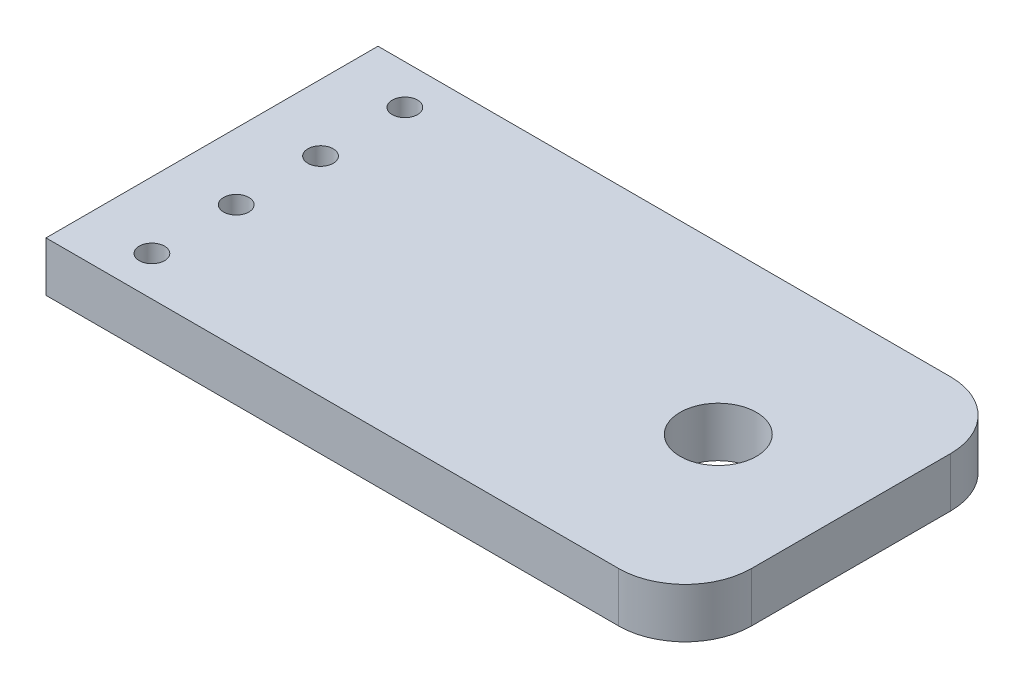
SolidWorks part; units mm, degrees
ref_plane "Front Plane" through (0, 0, 0) normal (0, 0, 1) x (1, 0, 0)
ref_plane "Top Plane" through (0, 0, 0) normal (0, 1, 0) x (1, 0, 0)
ref_plane "Right Plane" through (0, 0, 0) normal (1, 0, 0) x (0, 0, -1)
sketch "Sketch1" plane through (0, 0, 0) normal (0, 1, 0) x (1, 0, 0)
  line L0 (2, 8.81) -> (2, 1.19) construction
  line L1 (0, 0) -> (19.25, 0)
  line L2 (0, 0) -> (0, 10)
  line L3 (0, 10) -> (19.25, 10)
  line L4 (19.25, 0) -> (19.25, 10)
  circle A0 centre (15.25, 5) radius 1.15
  circle A1 centre (2, 6.27) radius 0.381
  circle A2 centre (2, 3.73) radius 0.381
  circle A3 centre (2, 1.19) radius 0.381
  circle A4 centre (2, 8.81) radius 0.381
  point P9 (0, 5)
  point P10 (2, 5)
  point P17 (16.3123, 3.49)
  point P18 (15.258, 5.1712)
  point P21 (19.25, 5)
  dimension "D3" = 2.3
  dimension "D5" = 2.54
  dimension "D7" = 0.762
  dimension "D8" = 0.762
  dimension "D1" = 10
  dimension "D2" = 19.25
  dimension "D4" = 2
  dimension "D6" = 2.54
  dimension "D9" = 2.54
  dimension "D10" = 4
extrude "Boss-Extrude1" add sketch "Sketch1" along normal blind 1.5
fillet "Fillet2" radius 2 2 edges at (19.25, 0.75, -10) (19.25, 0.75, 0)
